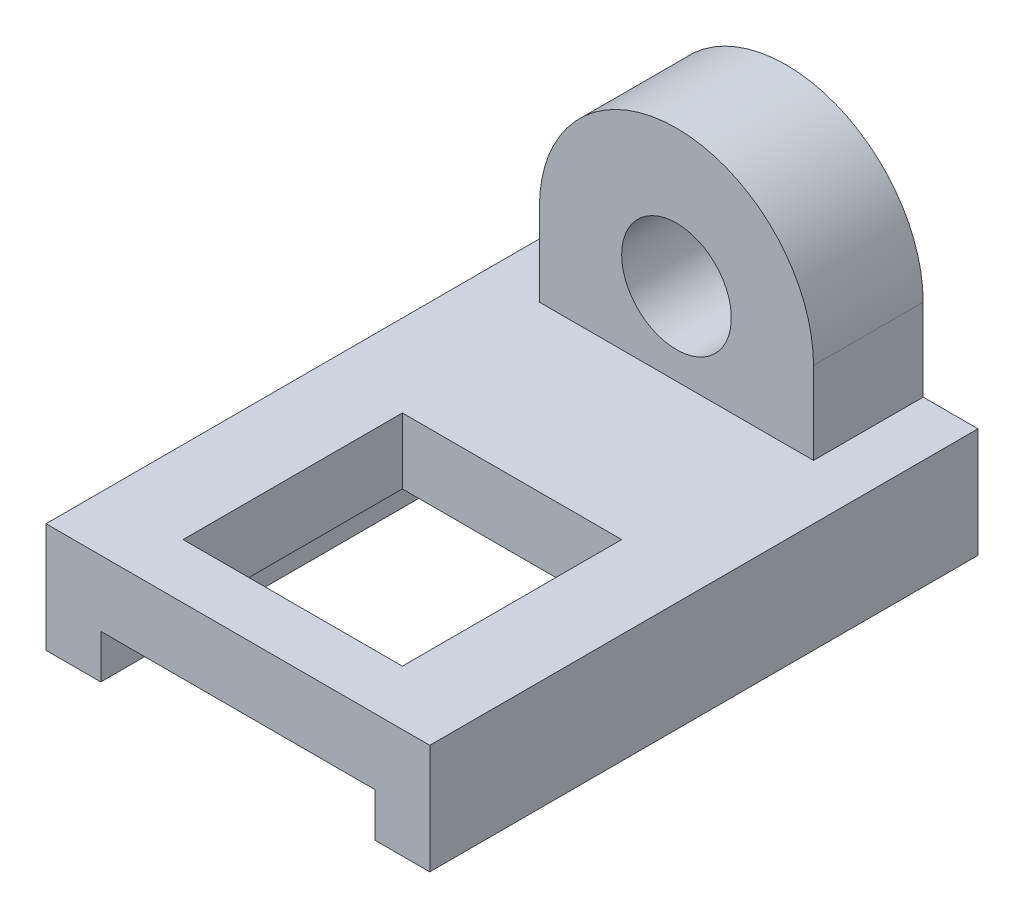
SolidWorks part; units mm, degrees
ref_plane "Спереди" through (0, 0, 0) normal (0, 0, 1) x (1, 0, 0)
ref_plane "Сверху" through (0, 0, 0) normal (0, 1, 0) x (1, 0, 0)
ref_plane "Справа" through (0, 0, 0) normal (1, 0, 0) x (0, 0, -1)
sketch "Эскиз1" plane through (0, 0, 0) normal (0, 0, 1) x (1, 0, 0)
  line L0 (0, 0) -> (0, 20)
  line L1 (0, 20) -> (70, 20)
  line L2 (70, 20) -> (70, 0)
  line L3 (70, 0) -> (60, 0)
  line L4 (60, 0) -> (60, 8)
  line L5 (60, 8) -> (10, 8)
  line L6 (10, 8) -> (10, 0)
  line L7 (10, 0) -> (0, 0)
  point P3 (0, 0)
  point P10 (0, 0)
  point P11 (0, 0)
  point P12 (0, 0)
  point P13 (13.0364, 11.0274)
  dimension "D1" = 70
  dimension "D2" = 50
  dimension "D3" = 20
  dimension "D4" = 8
extrude "Бобышка-Вытянуть1" add sketch "Эскиз1" along normal blind 100
sketch "Эскиз3" plane through (0, 0, 0) normal (0, 0, -1) x (-1, 0, 0)
  line L0 (-60, 20) -> (-60, 35)
  line L1 (-70, 20) -> (0, 20) construction
  line L2 (-35, 20) -> (-35, 48.7691) construction
  line L3 (-10, 20) -> (-10, 35)
  line L4 (-60, 20) -> (-10, 20)
  arc A0 (-60, 35) -> (-10, 35) centre (-35, 35) cw
  circle A1 centre (-35, 35) radius 10
  dimension "D1" = 20
  dimension "D2" = 25
  dimension "D3" = 40
extrude "Бобышка-Вытянуть2" add sketch "Эскиз3" against normal blind 20
sketch "Эскиз4" plane through (0, 20, 0) normal (0, 1, 0) x (1, 0, 0)
  line L0 (35, -70) -> (35, -100) construction
  line L1 (15, -90) -> (55, -90)
  line L2 (15, -90) -> (15, -50)
  line L3 (15, -50) -> (55, -50)
  line L4 (55, -90) -> (55, -50)
  line L5 (15, -90) -> (55, -50) construction
  line L6 (15, -50) -> (55, -90) construction
  line L8 (70, -100) -> (0, -100) construction
  point P0 (35, -70)
  point P9 (0, 0)
  point P10 (35.8892, -73.5496)
  dimension "D1" = 40
  dimension "D2" = 10
extrude "Вырез-Вытянуть1" cut sketch "Эскиз4" against normal up to surface (12 mm away) up to face at (35, 8, 50)
